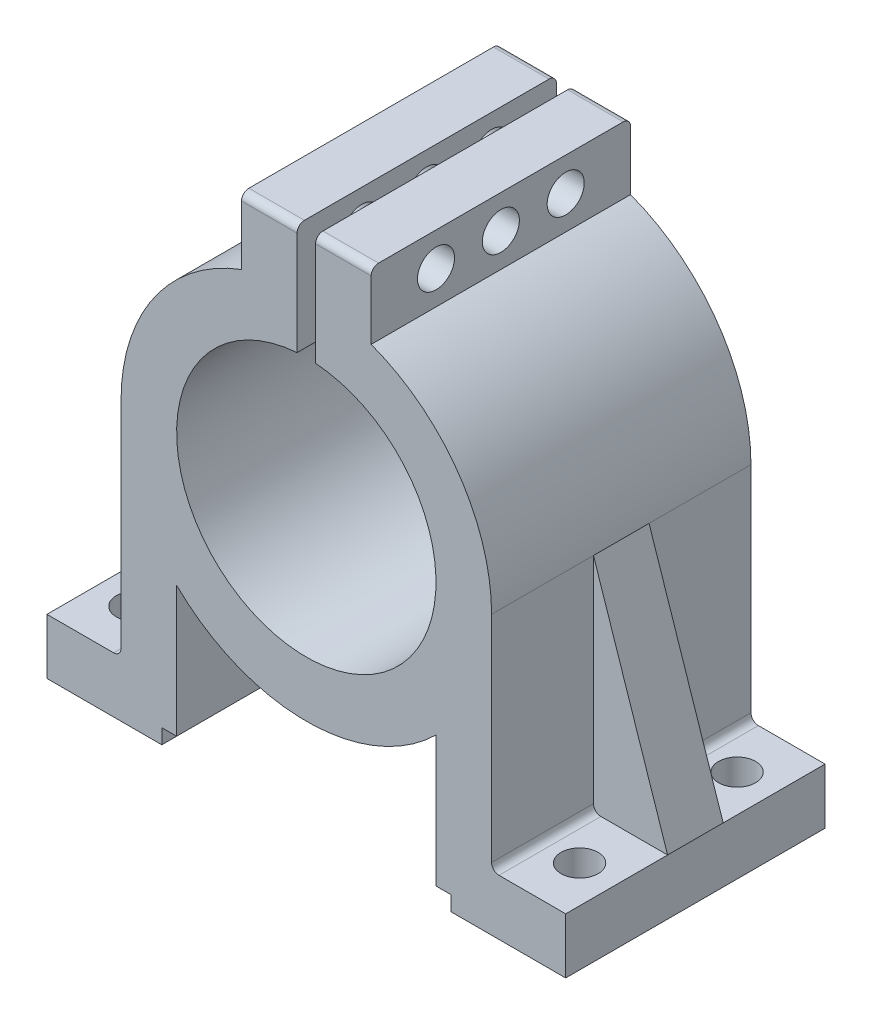
SolidWorks part; units mm, degrees
ref_plane "Front Plane" through (0, 0, 0) normal (0, 0, 1) x (1, 0, 0)
ref_plane "Top Plane" through (0, 0, 0) normal (0, 1, 0) x (1, 0, 0)
ref_plane "Right Plane" through (0, 0, 0) normal (1, 0, 0) x (0, 0, -1)
sketch "Sketch1" plane through (0, 0, 0) normal (0, 0, 1) x (1, 0, 0)
  circle A0 centre (0, 0) radius 20
  circle A1 centre (0, 0) radius 14
  dimension "D1" = 28
  dimension "D2" = 40
extrude "Boss-Extrude1" add sketch "Sketch1" along normal mid plane 28
sketch "Sketch2" plane through (0, 0, 14) normal (0, 0, 1) x (1, 0, 0)
  line L0 (-20, 0) -> (-20, -24)
  line L1 (-20, -24) -> (-28, -24)
  line L2 (-28, -24) -> (-28, -30)
  line L3 (-28, -30) -> (-14, -30)
  line L4 (-14, -30) -> (-14, -14.2829)
  line L5 (0, 27.7519) -> (0, -35.9812) construction
  line L6 (14, -30) -> (14, -14.2829)
  line L7 (28, -30) -> (14, -30)
  line L8 (28, -24) -> (28, -30)
  line L9 (20, -24) -> (28, -24)
  line L10 (20, 0) -> (20, -24)
  circle A0 centre (0, 0) radius 20 construction
  arc A1 (-20, 0) -> (-14, -14.2829) centre (0, 0) ccw
  arc A2 (20, 0) -> (14, -14.2829) centre (0, 0) cw
  dimension "D1" = 24
  dimension "D2" = 6
  dimension "D3" = 14
  dimension "D4" = 8
extrude "Boss-Extrude2" add sketch "Sketch2" against normal blind 28
sketch "Sketch3" plane through (0, 0, 14) normal (0, 0, 1) x (1, 0, 0)
  line L1 (-14, -30) -> (-15.6, -30)
  line L2 (-14, -30) -> (-14, -28.4)
  line L3 (-14, -28.4) -> (-15.6, -28.4)
  line L4 (-15.6, -30) -> (-15.6, -28.4)
  line L5 (14, -30) -> (15.6, -30)
  line L6 (14, -30) -> (14, -28.4)
  line L7 (14, -28.4) -> (15.6, -28.4)
  line L8 (15.6, -30) -> (15.6, -28.4)
  dimension "D1" = 1.6
  dimension "D2" = 1.6
  dimension "D3" = 1.6
  dimension "D4" = 1.6
extrude "Cut-Extrude1" cut sketch "Sketch3" against normal through all
fillet "Fillet1" radius 0.8 2 edges at (-20, -24, 0) (20, -24, 0)
sketch "Sketch4" plane through (0, 0, 0) normal (0, 0, 1) x (1, 0, 0)
  line L2 (-7, 18.735) -> (-7, 25.935)
  line L3 (-7, 25.935) -> (7, 25.935)
  line L4 (7, 18.735) -> (7, 25.935)
  arc A0 (20, 0) -> (-20, 0) centre (0, 0) ccw construction
  arc A1 (7, 18.735) -> (-7, 18.735) centre (0, 0) ccw
  point P7 (0, 25.935)
  dimension "D1" = 14
  dimension "D2" = 7.2
extrude "Boss-Extrude3" add sketch "Sketch4" along normal through all and the other way through all
sketch "Sketch5" plane through (0, 25.935, 0) normal (0, 1, 0) x (1, 0, 0)
  line L1 (-1, 0) -> (1, 0)
  line L2 (-1, 0) -> (-1, -28)
  line L3 (-1, -28) -> (1, -28)
  line L4 (1, 0) -> (1, -28)
  point P4 (0, 0)
  dimension "D1" = 2
extrude "Cut-Extrude2" cut sketch "Sketch5" against normal blind 25
sketch "Sketch6" plane through (7, 0, 0) normal (1, 0, 0) x (0, 0, -1)
  line L0 (-29.5799, 22.335) -> (3.6504, 22.335) construction
  line L2 (-14, 29.0973) -> (-14, 10.6235) construction
  line L3 (-14, 18.735) -> (-14, 25.935) construction
  circle A0 centre (0, 22.335) radius 2
  circle A1 centre (-7, 22.335) radius 2
  circle A2 centre (7, 22.335) radius 2
  dimension "D1" = 4
  dimension "D3" = 4
  dimension "D4" = 4
  dimension "D2" = 14
  dimension "D5" = 7
  dimension "D6" = 7
extrude "Cut-Extrude3" cut sketch "Sketch6" against normal through all
fillet "Fillet2" radius 0.8 2 edges at (4, 25.935, 14) (-4, 25.935, 14)
sketch "Sketch7" plane through (0, 0, 0) normal (0, 0, 1) x (1, 0, 0)
  line L0 (20, 0) -> (28, -24)
  line L1 (-23.6645, 0) -> (30.4631, 0) construction
  arc A0 (20, 0) -> (7, 18.735) centre (0, 0) ccw construction
rib "Rib1" sketch "Sketch7" sketch "Sketch7" thickness 6 extrusion direction parallel to sketch draft on no parameters "D1"=6
sketch "Sketch8" plane through (0, -24, 0) normal (0, 1, 0) x (1, 0, 0)
  line L0 (24, 17.8683) -> (24, -16.8607) construction
  line L1 (28, -3) -> (28, -14) construction
  line L2 (28, -14) -> (20.8, -14) construction
  line L3 (-31.4978, 0) -> (44.6574, 0) construction
  circle A0 centre (24, 8.5) radius 2
  circle A1 centre (24, -8.5) radius 2
  dimension "D1" = 4
  dimension "D3" = 4
  dimension "D2" = 5.5
extrude "Cut-Extrude4" cut sketch "Sketch8" against normal through all
mirror "Mirror1" about plane through (0, 0, 0) normal (1, 0, 0) of "Cut-Extrude4", "Rib1"
sketch "Sketch9" plane through (0, 25.935, 0) normal (0, 1, 0) x (1, 0, 0)
  line L0 (-7, 14) -> (7, 14) construction
  line L1 (-1, 0) -> (1, 0)
  line L2 (-1, 0) -> (-1, 14)
  line L3 (-1, 14) -> (1, 14)
  line L4 (1, 0) -> (1, 14)
  dimension "D1" = 2
extrude "Cut-Extrude5" cut sketch "Sketch9" against normal blind 31
